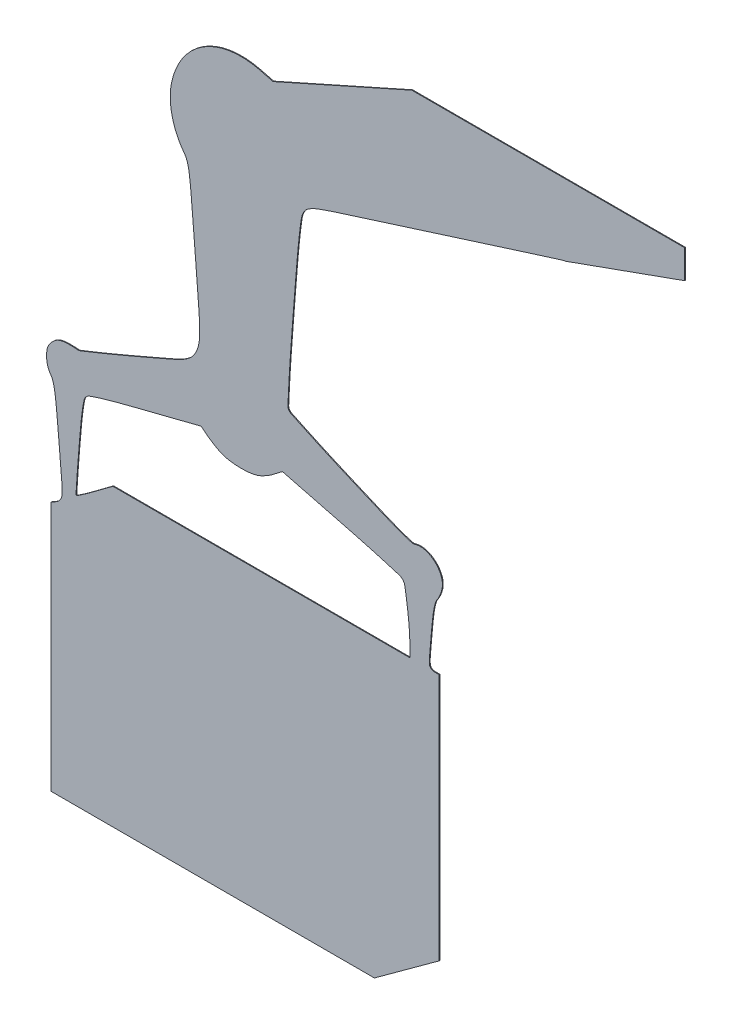
SolidWorks part; units mm, degrees
ref_plane "Front Plane" through (0, 0, 0) normal (0, 0, 1) x (1, 0, 0)
ref_plane "Top Plane" through (0, 0, 0) normal (0, 1, 0) x (1, 0, 0)
ref_plane "Right Plane" through (0, 0, 0) normal (1, 0, 0) x (0, 0, -1)
sketch "Sketch1" plane through (0, 0, 0) normal (0, 0, 1) x (1, 0, 0)
  line L0 (8013.7, 12087.9382) -> (6413.5, 11374.204)
  line L1 (6413.5, 11374.204) -> (6240.4799, 11418.3284)
  line L2 (3581.4, 5198.3404) -> (3505.2, 5153.328)
  line L3 (3505.2, 5153.328) -> (3505.2, 3516.464)
  line L4 (3505.2, 3516.464) -> (3505.2, 1879.6)
  line L5 (3505.2, 1879.6) -> (5622.3957, 1879.6)
  line L6 (5622.3957, 1879.6) -> (7739.5913, 1879.6)
  line L7 (7739.5913, 1879.6) -> (8162.3957, 2187.757)
  line L8 (8162.3957, 2187.757) -> (8585.2, 2495.9141)
  line L9 (8585.2, 2495.9141) -> (8585.2, 4118.157)
  line L10 (8585.2, 4118.157) -> (8585.2, 5740.4)
  line L11 (8585.2, 5740.4) -> (8521.7, 5740.4)
  line L12 (8585.2, 10732.9427) -> (9724.6877, 11094.0807)
  line L13 (11325.3923, 10020.3) -> (11488.731, 9831.6199)
  line L14 (11488.731, 9831.6199) -> (11633.909, 9664.1613)
  line L15 (11633.909, 9664.1613) -> (11756.8075, 9522.5883)
  line L16 (12065, 5921.1421) -> (12065, 5746.2841)
  line L17 (12065, 5746.2841) -> (11728.45, 5735.6247)
  line L18 (10878.3065, 5287.2778) -> (10807.7, 5143.5)
  line L19 (10807.7, 5143.5) -> (10800.0791, 4298.95)
  line L20 (10800.0791, 4298.95) -> (10792.4582, 3454.4)
  line L21 (10792.4582, 3454.4) -> (10695.5545, 3454.4)
  line L22 (10531.7254, 3401.7565) -> (10464.8, 3349.1129)
  line L23 (10464.8, 3349.1129) -> (10464.8, 2906.3588)
  line L24 (10464.8, 2906.3588) -> (10464.8, 2463.6046)
  line L25 (10464.8, 2463.6046) -> (13671.55, 2470.0523)
  line L26 (13671.55, 2470.0523) -> (16878.3, 2476.5)
  line L27 (16878.3, 2476.5) -> (16878.3, 2904.1918)
  line L28 (16878.3, 2904.1918) -> (16878.3, 3331.8836)
  line L29 (16878.3, 3331.8836) -> (16807.0336, 3393.1418)
  line L30 (16650.3866, 3454.4) -> (16565.006, 3454.4)
  line L31 (16565.006, 3454.4) -> (16556.553, 4288.879)
  line L32 (16556.553, 4288.879) -> (16548.1, 5123.358)
  line L33 (16548.1, 5123.358) -> (16459.2, 5297.5729)
  line L34 (15549.4837, 5740.4) -> (15265.4, 5740.4)
  line L35 (15265.4, 5740.4) -> (15265.4, 5904.521)
  line L36 (15265.4, 5904.521) -> (15265.4, 6068.642)
  line L37 (15265.4, 6068.642) -> (15365.7226, 6095.656)
  line L38 (13392.4905, 11080.3188) -> (13249.1836, 11204.4862)
  line L39 (13249.1836, 11204.4862) -> (12978.5872, 11438.7764)
  line L40 (12978.5872, 11438.7764) -> (12661.0677, 11713.6338)
  line L41 (12661.0677, 11713.6338) -> (12331.7, 11998.6859)
  line L42 (6416.8526, 6925.3764) -> (6535.7005, 7016.0951)
  line L43 (6535.7005, 7016.0951) -> (7300.1003, 6820.8399)
  line L44 (8204.2, 5847.005) -> (8204.2, 5740.4)
  line L45 (8204.2, 5740.4) -> (6261.0664, 5740.4)
  line L46 (6261.0664, 5740.4) -> (4317.9329, 5740.4)
  line L47 (4317.9329, 5740.4) -> (4083.0164, 5565.3869)
  line L48 (4740.2597, 6813.0046) -> (5473.7, 6998.8611)
  line L49 (5473.7, 6998.8611) -> (5549.9, 6937.2032)
  arc A0 (10252.0935, 13323.4899) -> (10114.6709, 13270.5908) centre (10485.9798, 12510.9446) ccw
  arc A1 (10114.6709, 13270.5908) -> (9972.416, 13189.4765) centre (10680.5693, 12112.8443) ccw
  arc A2 (9972.416, 13189.4765) -> (9841.3535, 13090.8097) centre (10682.7363, 12109.5526) ccw
  arc A3 (9841.3535, 13090.8097) -> (9737.5944, 12985.0784) centre (10402.6249, 12436.2301) ccw
  arc A4 (9737.5944, 12985.0784) -> (9696.7306, 12934.3409) centre (11838.9299, 11250.8474) ccw
  arc A5 (9696.7306, 12934.3409) -> (9660.7452, 12887.0372) centre (11182.0651, 11767.0583) ccw
  arc A6 (9660.7452, 12887.0372) -> (9631.8231, 12846.7566) centre (11340.1137, 11650.7039) ccw
  arc A7 (9631.8231, 12846.7566) -> (9623.2944, 12829.8192) centre (9685.8203, 12808.9505) ccw
  arc A8 (9608.6668, 12813.478) -> (9623.2944, 12829.8192) centre (9597.0774, 12838.5694) ccw
  arc A9 (9146.6008, 12600.2811) -> (9608.6668, 12813.478) centre (-255792.6689, 587415.7862) ccw
  arc A10 (8627.9063, 12363.6155) -> (9146.6008, 12600.2811) centre (-21976.6937, 80125.7388) ccw
  arc A11 (8013.7, 12087.9382) -> (8627.9063, 12363.6155) centre (-50634.9118, 143578.5359) ccw
  arc A12 (6240.4799, 11418.3284) -> (5850.1835, 11439.2224) centre (5992.7754, 10447.0343) ccw
  arc A13 (5850.1835, 11439.2224) -> (5494.1407, 11306.9205) centre (5977.9589, 10550.1298) ccw
  arc A14 (5494.1407, 11306.9205) -> (5225.1613, 11039.5959) centre (5976.1825, 10552.9105) ccw
  arc A15 (5225.1613, 11039.5959) -> (5081.729, 10677.5348) centre (6056.6861, 10500.7418) ccw
  arc A16 (5081.729, 10677.5348) -> (5069.2279, 10499.192) centre (5887.2837, 10531.4592) ccw
  arc A17 (5069.2279, 10499.192) -> (5094.762, 10316.1951) centre (6001.1767, 10535.9499) ccw
  arc A18 (5094.762, 10316.1951) -> (5155.9621, 10141.4417) centre (6005.0064, 10536.8769) ccw
  arc A19 (5155.9621, 10141.4417) -> (5249.0238, 9987.4979) centre (5913.2895, 10494.1589) ccw
  arc A20 (5290.0091, 9907.7948) -> (5249.0238, 9987.4979) centre (5046.2606, 9832.8428) ccw
  arc A21 (5315.7822, 9792.197) -> (5290.0091, 9907.7948) centre (4572.3498, 9687.1167) ccw
  arc A22 (5339.6477, 9581.5701) -> (5315.7822, 9792.197) centre (1511.3526, 9254.463) ccw
  arc A23 (5387.4374, 9008.2307) -> (5339.6477, 9581.5701) centre (-132723.8185, -2215.1229) ccw
  arc A24 (5444.2516, 8287.1951) -> (5387.4374, 9008.2307) centre (-141614.0357, -2937.5546) ccw
  arc A25 (5453.9529, 8037.2024) -> (5444.2516, 8287.1951) centre (2108.123, 8032.5479) ccw
  arc A26 (5437.7012, 7894.2959) -> (5453.9529, 8037.2024) centre (4825.2122, 8036.3273) ccw
  arc A27 (5389.1535, 7775.4147) -> (5437.7012, 7894.2959) centre (5044.7167, 7985.4263) ccw
  arc A28 (5326.0361, 7700.1996) -> (5389.1535, 7775.4147) centre (5109.8117, 7945.7364) ccw
  arc A29 (5237.7634, 7638.9825) -> (5326.0361, 7700.1996) centre (5018.422, 8049.5155) ccw
  arc A30 (5073.2949, 7559.3773) -> (5237.7634, 7638.9825) centre (4159.0171, 9658.0261) ccw
  arc A31 (4610.1, 7359.1782) -> (5073.2949, 7559.3773) centre (-29746.8689, 87485.8651) ccw
  arc A32 (4334.7458, 7242.4947) -> (4610.1, 7359.1782) centre (-9242.0821, 39664.8458) ccw
  arc A33 (4096.6231, 7144.6356) -> (4334.7458, 7242.4947) centre (-3146.485, 25108.1009) ccw
  arc A34 (3889.0491, 7061.3988) -> (4096.6231, 7144.6356) centre (-17819.7268, 61498.6719) ccw
  arc A35 (3860.8, 7057.0498) -> (3889.0491, 7061.3988) centre (3865.4977, 7120.4567) ccw
  arc A36 (3860.8, 7057.0498) -> (3716.4797, 7061.0921) centre (3744.687, 5489.8355) ccw
  arc A37 (3716.4797, 7061.0921) -> (3622.0311, 7045.2863) centre (3722.3132, 6736.1395) ccw
  arc A38 (3622.0311, 7045.2863) -> (3551.7445, 7005.9035) centre (3685.5189, 6849.5675) ccw
  arc A39 (3551.7445, 7005.9035) -> (3488.5769, 6936.3069) centre (3794.8768, 6721.766) ccw
  arc A40 (3488.5769, 6936.3069) -> (3457.805, 6864.6105) centre (3645.0925, 6826.6792) ccw
  arc A41 (3457.805, 6864.6105) -> (3450.4111, 6771.1586) centre (3838.8017, 6787.4475) ccw
  arc A42 (3450.4111, 6771.1586) -> (3465.7418, 6676.7762) centre (3852.3965, 6788.0174) ccw
  arc A43 (3465.7418, 6676.7762) -> (3502.5934, 6602.0933) centre (3691.4327, 6741.7079) ccw
  arc A44 (3533.979, 6539.0185) -> (3502.5934, 6602.0933) centre (3339.8314, 6481.7581) ccw
  arc A45 (3556.1691, 6441.2229) -> (3533.979, 6539.0185) centre (2778.2021, 6316.1153) ccw
  arc A46 (3577.1122, 6278.5056) -> (3556.1691, 6441.2229) centre (980.0302, 6026.9454) ccw
  arc A47 (3607.2203, 5951.4839) -> (3577.1122, 6278.5056) centre (-30816.4909, 2947.0655) ccw
  arc A48 (3649.7229, 5451.7678) -> (3607.2203, 5951.4839) centre (-109531.738, -3923.0241) ccw
  arc A49 (3652.9653, 5317.7275) -> (3649.7229, 5451.7678) centre (2506.1316, 5357.0445) ccw
  arc A50 (3632.6405, 5249.1507) -> (3652.9653, 5317.7275) centre (3510.6509, 5322.6064) ccw
  arc A51 (3581.4, 5198.3404) -> (3632.6405, 5249.1507) centre (3506.5281, 5325.0886) ccw
  arc A52 (8480.1587, 5755.3705) -> (8521.7, 5740.4) centre (8521.7, 5805.5215) ccw
  arc A53 (8460.9594, 5792.4048) -> (8480.1587, 5755.3705) centre (8514.2653, 5796.5458) ccw
  arc A54 (8461.1407, 5879.9232) -> (8460.9594, 5792.4048) centre (9009.628, 5835.0276) ccw
  arc A55 (8487.1696, 6184.9) -> (8461.1407, 5879.9232) centre (52418.8007, 2281.8604) ccw
  arc A56 (8503.998, 6351.1916) -> (8487.1696, 6184.9) centre (15286.0693, 5580.8609) ccw
  arc A57 (8520.8311, 6459.8446) -> (8503.998, 6351.1916) centre (9849.6243, 6198.3509) ccw
  arc A58 (8540.4302, 6534.7426) -> (8520.8311, 6459.8446) centre (9137.479, 6338.4948) ccw
  arc A59 (8566.1292, 6586.1394) -> (8540.4302, 6534.7426) centre (8727.9397, 6473.1088) ccw
  arc A60 (8566.1292, 6586.1394) -> (8586.0423, 6620.1363) centre (8363.7479, 6727.511) ccw
  arc A61 (8586.0423, 6620.1363) -> (8604.792, 6663.9413) centre (8114.9065, 6847.7095) ccw
  arc A62 (8604.792, 6663.9413) -> (8619.7439, 6710.0428) centre (8103.2991, 6852.0638) ccw
  arc A63 (8619.7439, 6710.0428) -> (8628.0625, 6751.2394) centre (8326.364, 6790.7217) ccw
  arc A64 (8628.0625, 6751.2394) -> (8609.9912, 6880.2982) centre (8385.1807, 6783.0247) ccw
  arc A65 (8609.9912, 6880.2982) -> (8527.689, 6993.646) centre (8315.0012, 6752.6589) ccw
  arc A66 (8527.689, 6993.646) -> (8405.7893, 7060.4322) centre (8318.7225, 6756.8759) ccw
  arc A67 (8405.7893, 7060.4322) -> (8277.7285, 7060.4338) centre (8341.7561, 6837.1824) ccw
  arc A68 (8215.0088, 7061.0271) -> (8277.7285, 7060.4338) centre (8247.3673, 7166.2973) ccw
  arc A69 (8070.9305, 7109.9044) -> (8215.0088, 7061.0271) centre (8990.1228, 9582.6636) ccw
  arc A70 (7843.5906, 7199.8569) -> (8070.9305, 7109.9044) centre (10111.8858, 12600.338) ccw
  arc A71 (7427.6986, 7376.4141) -> (7843.5906, 7199.8569) centre (30708.8976, 61638.692) ccw
  arc A72 (7126.0979, 7507.9948) -> (7427.6986, 7376.4141) centre (18086.9105, 32220.2071) ccw
  arc A73 (6867.7759, 7625.5064) -> (7126.0979, 7507.9948) centre (13210.3966, 21225.6068) ccw
  arc A74 (6646.295, 7729.6413) -> (6867.7759, 7625.5064) centre (23423.9194, 43125.7729) ccw
  arc A75 (6619.656, 7753.2583) -> (6646.295, 7729.6413) centre (6673.6257, 7787.3015) ccw
  arc A76 (6608.2654, 7796.0011) -> (6619.656, 7753.2583) centre (6682.488, 7792.8917) ccw
  arc A77 (6619.9588, 8045.1713) -> (6608.2654, 7796.0011) centre (31411.9392, 6756.8423) ccw
  arc A78 (6640.9084, 8384.4014) -> (6619.9588, 8045.1713) centre (24012.1758, 7141.3547) ccw
  arc A79 (6678.9754, 8894.7506) -> (6640.9084, 8384.4014) centre (91266.7116, 2328.7473) ccw
  arc A80 (6725.5817, 9475.2788) -> (6678.9754, 8894.7506) centre (116567.3834, 364.7551) ccw
  arc A81 (6756.6674, 9797.1308) -> (6725.5817, 9475.2788) centre (18632.8341, 8487.6592) ccw
  arc A82 (6782.8885, 9999.8092) -> (6756.6674, 9797.1308) centre (12147.669, 9202.7171) ccw
  arc A83 (6810.5265, 10087.8443) -> (6782.8885, 9999.8092) centre (7075.3066, 9956.3622) ccw
  arc A84 (6877.5131, 10162.6919) -> (6810.5265, 10087.8443) centre (6979.7001, 10003.8379) ccw
  arc A85 (7000.4666, 10223.631) -> (6877.5131, 10162.6919) centre (7211.1499, 9644.0393) ccw
  arc A86 (7268.1977, 10314.8144) -> (7000.4666, 10223.631) centre (9369.4248, 3706.5838) ccw
  arc A87 (8585.2, 10732.9427) -> (7268.1977, 10314.8144) centre (480922.4875, -1479297.7053) ccw
  arc A88 (10039.6335, 11193.3354) -> (9724.6877, 11094.0807) centre (41776.314, -90059.8862) ccw
  arc A89 (10213.2818, 11247.4404) -> (10039.6335, 11193.3354) centre (26096.0439, -40033.4917) ccw
  arc A90 (10240.8074, 11251.8723) -> (10213.2818, 11247.4404) centre (10242.6891, 11152.4925) ccw
  arc A91 (10260.5056, 11243.2311) -> (10240.8074, 11251.8723) centre (10241.2933, 11226.2078) ccw
  arc A92 (10436.4002, 11044.1096) -> (10260.5056, 11243.2311) centre (-55151.9765, -46716.3766) ccw
  arc A93 (10710.0413, 10730.9018) -> (10436.4002, 11044.1096) centre (-29133.5032, -23803.1693) ccw
  arc A94 (11325.3923, 10020.3) -> (10710.0413, 10730.9018) centre (-782064.5862, -676399.9684) ccw
  arc A95 (11756.8075, 9522.5883) -> (11789.3396, 9485.6066) centre (14689.5852, 12069.6981) ccw
  arc A96 (11812.1705, 9454.6385) -> (11789.3396, 9485.6066) centre (11633.8921, 9347.1044) ccw
  arc A97 (11822.1641, 9426.8225) -> (11812.1705, 9454.6385) centre (11747.7883, 9415.8045) ccw
  arc A98 (11821.5624, 9394.1164) -> (11822.1641, 9426.8225) centre (11723.9364, 9412.2711) ccw
  arc A99 (11810.0346, 9345.9066) -> (11821.5624, 9394.1164) centre (11342.1585, 9483.2666) ccw
  arc A100 (11810.0346, 9345.9066) -> (11782.3343, 9160.164) centre (12467.2666, 9152.9551) ccw
  arc A101 (11782.3343, 9160.164) -> (11769.9325, 7807.8605) centre (511149.4342, 3904.3043) ccw
  arc A102 (11769.9325, 7807.8605) -> (11760.8652, 6444.787) centre (597277.8939, 3231.462) ccw
  arc A103 (11760.8652, 6444.787) -> (11786.1076, 6284.962) centre (12262.0517, 6442.0373) ccw
  arc A104 (11786.1076, 6284.962) -> (11821.5015, 6213.5927) centre (12054.1125, 6373.4113) ccw
  arc A105 (11821.5015, 6213.5927) -> (11876.4599, 6152.2101) centre (12086.9828, 6395.9953) ccw
  arc A106 (11876.4599, 6152.2101) -> (11941.1162, 6110.2415) centre (12061.4872, 6366.4716) ccw
  arc A107 (11941.1162, 6110.2415) -> (12004.9254, 6096) centre (12004.9254, 6246.07) ccw
  arc A108 (12038.9372, 6089.5184) -> (12004.9254, 6096) centre (12004.9254, 6003.522) ccw
  arc A109 (12056.4684, 6071.1672) -> (12038.9372, 6089.5184) centre (12027.7812, 6061.3114) ccw
  arc A110 (12063.6881, 6030.9017) -> (12056.4684, 6071.1672) centre (11929.9621, 6027.7043) ccw
  arc A111 (12065, 5921.1421) -> (12063.6881, 6030.9017) centre (7472.8247, 5921.1403) ccw
  arc A112 (11728.45, 5735.6247) -> (11550.417, 5727.8291) centre (11961.6078, -1625.9564) ccw
  arc A113 (11550.417, 5727.8291) -> (11435.3917, 5716.5779) centre (11627.9007, 4342.0797) ccw
  arc A114 (11435.3917, 5716.5779) -> (11350.1207, 5699.1338) centre (11531.825, 5028.0536) ccw
  arc A115 (11350.1207, 5699.1338) -> (11274.4909, 5672.0445) centre (11482.2723, 5211.0652) ccw
  arc A116 (11274.4909, 5672.0445) -> (11154.2429, 5604.1277) centre (11587.8603, 4976.8094) ccw
  arc A117 (11154.2429, 5604.1277) -> (11044.3142, 5513.8063) centre (11642.236, 4898.1424) ccw
  arc A118 (11044.3142, 5513.8063) -> (10950.5394, 5406.2939) centre (11645.4647, 4894.816) ccw
  arc A119 (10950.5394, 5406.2939) -> (10878.3065, 5287.2778) centre (11581.2624, 4942.0696) ccw
  arc A120 (10695.5545, 3454.4) -> (10651.0085, 3450.8331) centre (10695.5546, 3174.4539) ccw
  arc A121 (10651.0085, 3450.8331) -> (10606.7287, 3440.2148) centre (10699.0047, 3153.048) ccw
  arc A122 (10606.7287, 3440.2148) -> (10565.9141, 3423.5009) centre (10693.5689, 3169.9638) ccw
  arc A123 (10565.9141, 3423.5009) -> (10531.7254, 3401.7565) centre (10657.1373, 3242.3212) ccw
  arc A124 (16807.0336, 3393.1418) -> (16771.4902, 3418.8051) centre (16638.067, 3196.5702) ccw
  arc A125 (16771.4902, 3418.8051) -> (16732.0332, 3438.1938) centre (16636.5676, 3194.0731) ccw
  arc A126 (16732.0332, 3438.1938) -> (16690.9027, 3450.321) centre (16641.1762, 3205.858) ccw
  arc A127 (16690.9027, 3450.321) -> (16650.3866, 3454.4) centre (16650.3868, 3251.1402) ccw
  arc A128 (16459.2, 5297.5729) -> (16314.3837, 5504.6466) centre (15643.7069, 4881.4355) ccw
  arc A129 (16314.3837, 5504.6466) -> (16130.4, 5640.928) centre (15857.3197, 5079.9297) ccw
  arc A130 (16130.4, 5640.928) -> (15884.5429, 5716.4253) centre (15766.0031, 4892.3347) ccw
  arc A131 (15884.5429, 5716.4253) -> (15549.4837, 5740.4) centre (15549.483, 3387.088) ccw
  arc A132 (15365.7226, 6095.656) -> (15410.5662, 6111.7521) centre (15289.7122, 6377.9358) ccw
  arc A133 (15410.5662, 6111.7521) -> (15452.9987, 6135.1424) centre (15281.3646, 6396.3212) ccw
  arc A134 (15452.9987, 6135.1424) -> (15489.875, 6163.8537) centre (15292.7314, 6379.0246) ccw
  arc A135 (15489.875, 6163.8537) -> (15518.1226, 6195.8061) centre (15352.6349, 6313.6435) ccw
  arc A136 (15518.1226, 6195.8061) -> (15550.2306, 6279.2645) centre (15371.7777, 6300.0131) ccw
  arc A137 (15550.2306, 6279.2645) -> (15563.3097, 6453.967) centre (13428.7054, 6525.9335) ccw
  arc A138 (15563.3097, 6453.967) -> (15569.2132, 6784.0631) centre (5132.7208, 6805.6094) ccw
  arc A139 (15569.2132, 6784.0631) -> (15570.2, 7740.508) centre (-447823.9797, 7740.406) ccw
  arc A140 (15570.2, 7740.508) -> (15566.205, 8841.1327) centre (-136032.4961, 7740.5483) ccw
  arc A141 (15566.205, 8841.1327) -> (15544.1483, 9254.4713) centre (11070.5982, 8808.4942) ccw
  arc A142 (15544.1483, 9254.4713) -> (15485.8152, 9528.862) centre (14274.0208, 9127.8492) ccw
  arc A143 (15485.8152, 9528.862) -> (15361.9134, 9829.8) centre (13307.7318, 8808.0795) ccw
  arc A144 (15361.9134, 9829.8) -> (15295.8502, 9950.7613) centre (13751.7327, 9028.9181) ccw
  arc A145 (15295.8502, 9950.7613) -> (15227.9328, 10051.2647) centre (14366.556, 9395.9707) ccw
  arc A146 (15227.9328, 10051.2647) -> (15140.8281, 10155.1889) centre (14085.0351, 9181.8031) ccw
  arc A147 (15140.8281, 10155.1889) -> (15011.8922, 10289.8997) centre (11472.4681, 6773.1475) ccw
  arc A148 (15011.8922, 10289.8997) -> (14870.9251, 10426.7982) centre (11107.8805, 6410.8905) ccw
  arc A149 (14870.9251, 10426.7982) -> (14769.5661, 10511.6839) centre (14059.3937, 9560.7346) ccw
  arc A150 (14769.5661, 10511.6839) -> (14667.4575, 10578.1698) centre (14202.097, 9751.8201) ccw
  arc A151 (14667.4575, 10578.1698) -> (14528.3784, 10650.9897) centre (13406.3021, 8338.7078) ccw
  arc A152 (14528.3784, 10650.9897) -> (14342.7936, 10732.1781) centre (13405.938, 8337.9594) ccw
  arc A153 (14342.7936, 10732.1781) -> (14166.8032, 10790.8401) centre (13682.8845, 9045.7238) ccw
  arc A154 (14166.8032, 10790.8401) -> (13989.2088, 10830.1871) centre (13703.3883, 9119.6589) ccw
  arc A155 (13989.2088, 10830.1871) -> (13798.8905, 10853.2754) centre (13636.7725, 8720.9838) ccw
  arc A156 (13696.5101, 10866.9445) -> (13798.8905, 10853.2754) centre (13867.8067, 11759.6995) ccw
  arc A157 (13628.8842, 10891.5933) -> (13696.5101, 10866.9445) centre (13739.0895, 11088.857) ccw
  arc A158 (13553.9989, 10943.0508) -> (13628.8842, 10891.5933) centre (13868.5679, 11320.6198) ccw
  arc A159 (13392.4905, 11080.3188) -> (13553.9989, 10943.0508) centre (20463.7071, 19236.6031) ccw
  arc A160 (11948.983, 12332.8993) -> (12331.7, 11998.6859) centre (49274.9761, 54689.6872) ccw
  arc A161 (11691.2791, 12566.2248) -> (11948.983, 12332.8993) centre (20497.4202, 22033.4743) ccw
  arc A162 (11514.9817, 12735.1871) -> (11691.2791, 12566.2248) centre (17265.0916, 18558.4665) ccw
  arc A163 (11446.9252, 12821.6767) -> (11514.9817, 12735.1871) centre (11825.017, 13049.1667) ccw
  arc A164 (11446.9252, 12821.6767) -> (11280.838, 13038.5976) centre (10397.7407, 12190.4035) ccw
  arc A165 (11280.838, 13038.5976) -> (11077.6061, 13202.0415) centre (10545.4808, 12332.3037) ccw
  arc A166 (11077.6061, 13202.0415) -> (10842.7129, 13306.545) centre (10561.9295, 12359.1884) ccw
  arc A167 (10842.7129, 13306.545) -> (10583.3984, 13350.0022) centre (10535.9778, 12271.6281) ccw
  arc A168 (10583.3984, 13350.0022) -> (10488.6588, 13351.4324) centre (10511.2508, 11709.3518) ccw
  arc A169 (10488.6588, 13351.4324) -> (10398.208, 13347.1957) centre (10507.5068, 11981.3768) ccw
  arc A170 (10398.208, 13347.1957) -> (10317.3298, 13337.797) centre (10488.8534, 12214.4726) ccw
  arc A171 (10317.3298, 13337.797) -> (10252.0935, 13323.4899) centre (10395.6874, 12824.6284) ccw
  arc A172 (5727.7, 6829.2305) -> (5826.5113, 6798.3403) centre (5900.303, 7207.8678) ccw
  arc A173 (5826.5113, 6798.3403) -> (5953.5319, 6784.1763) centre (5995.214, 7734.6095) ccw
  arc A174 (5953.5319, 6784.1763) -> (6086.2648, 6787.1201) centre (5997.6295, 7789.7097) ccw
  arc A175 (6086.2648, 6787.1201) -> (6203.3524, 6808.3705) centre (6028.8325, 7436.7617) ccw
  arc A176 (6203.3524, 6808.3705) -> (6247.9783, 6824.7617) centre (6124.841, 7091.066) ccw
  arc A177 (6247.9783, 6824.7617) -> (6305.1122, 6853.5845) centre (5854.2202, 7676.3265) ccw
  arc A178 (6305.1122, 6853.5845) -> (6364.4144, 6888.7157) centre (5810.3766, 7756.3264) ccw
  arc A179 (6364.4144, 6888.7157) -> (6416.8526, 6925.3764) centre (5952.7186, 7533.4239) ccw
  arc A180 (7616.8024, 6737.8543) -> (7300.1003, 6820.8399) centre (744.4734, -18843.5583) ccw
  arc A181 (7867.4556, 6667.2421) -> (7616.8024, 6737.8543) centre (4835.4283, -3615.4145) ccw
  arc A182 (8067.0813, 6606.9903) -> (7867.4556, 6667.2421) centre (3249.8214, -8992.6717) ccw
  arc A183 (8106.5513, 6583.0423) -> (8067.0813, 6606.9903) centre (8039.0959, 6516.3657) ccw
  arc A184 (8137.7779, 6521.845) -> (8106.5513, 6583.0423) centre (8025.9029, 6503.325) ccw
  arc A185 (8170.8196, 6300.1854) -> (8137.7779, 6521.845) centre (1261.4887, 5383.5388) ccw
  arc A186 (8195.929, 6060.9752) -> (8170.8196, 6300.1854) centre (3805.2957, 5721.0231) ccw
  arc A187 (8204.2, 5847.005) -> (8195.929, 6060.9752) centre (5432.3326, 5847.0033) ccw
  arc A188 (3992.2777, 5498.904) -> (4083.0164, 5565.3869) centre (-134.1554, 11226) ccw
  arc A189 (3914.379, 5444.3147) -> (3992.2777, 5498.904) centre (1872.3995, 8441.0894) ccw
  arc A190 (3846.4682, 5398.3879) -> (3914.379, 5444.3147) centre (-2684.2836, 15128.413) ccw
  arc A191 (3838.8142, 5398.9894) -> (3846.4682, 5398.3879) centre (3843.0211, 5403.5236) ccw
  arc A192 (3835.4262, 5407.4754) -> (3838.8142, 5398.9894) centre (3846.0639, 5406.8031) ccw
  arc A193 (3845.7389, 5568.6876) -> (3835.4262, 5407.4754) centre (109901.2083, -1296.575) ccw
  arc A194 (3858.4982, 5750.4205) -> (3845.7389, 5568.6876) centre (20524.7365, 4488.9839) ccw
  arc A195 (3875.4274, 5964.5869) -> (3858.4982, 5750.4205) centre (35946.9251, 3321.6807) ccw
  arc A196 (3900.5044, 6248.55) -> (3875.4274, 5964.5869) centre (28108.4279, 3967.6421) ccw
  arc A197 (3920.6727, 6417.0114) -> (3900.5044, 6248.55) centre (7250.9541, 5932.8698) ccw
  arc A198 (3940.3373, 6525.0037) -> (3920.6727, 6417.0114) centre (5439.9816, 6196.1433) ccw
  arc A199 (3964.0729, 6574.3585) -> (3940.3373, 6525.0037) centre (4056.4751, 6499.5357) ccw
  arc A200 (4011.6208, 6608.2203) -> (3964.0729, 6574.3585) centre (4048.7157, 6505.8189) ccw
  arc A201 (4151.4563, 6655.0134) -> (4011.6208, 6608.2203) centre (5031.2387, 3793.5541) ccw
  arc A202 (4369.3058, 6717.1608) -> (4151.4563, 6655.0134) centre (5784.0414, 1345.1004) ccw
  arc A203 (4740.2597, 6813.0046) -> (4369.3058, 6717.1608) centre (14833.9848, -33019.5514) ccw
  arc A204 (5549.9, 6937.2032) -> (5586.372, 6910.2467) centre (5875.5703, 7339.682) ccw
  arc A205 (5586.372, 6910.2467) -> (5633.5612, 6880.0523) centre (6253.2435, 7900.4927) ccw
  arc A206 (5633.5612, 6880.0523) -> (5683.2467, 6851.4439) centre (6271.6551, 7930.8083) ccw
  arc A207 (5683.2467, 6851.4439) -> (5727.7, 6829.2305) centre (6016.4694, 7462.6995) ccw
extrude "Boss-Extrude1" add sketch "Sketch1" along normal blind 10
scale "Scale1" bodies to scale 101 scale about centroid uniform scaling yes scale factor 0.046
sketch "Sketch2" plane through (0, 0, 5.23) normal (0, 0, 1) x (1, 0, 0)
  line L0 (10322.0306, 6841.4546) -> (10418.1131, 6875.8933)
  line L1 (10433.3626, 6862.6956) -> (10418.2116, 6875.808) construction
  line L2 (10322.0306, 6841.4546) -> (10292.0281, 6387.3884)
  line L3 (10292.0281, 6387.3884) -> (10677.2596, 6410.0491)
  line L4 (10677.2596, 6410.0491) -> (10661.0672, 6685.3199)
  line L5 (10661.0672, 6685.3199) -> (10558.9205, 6841.4546)
  line L6 (10558.9205, 6841.4546) -> (10418.1131, 6875.8933)
  arc A0 (10322.0306, 6841.4546) -> (10320.7644, 6841.2507) centre (10322.1171, 6836.8831) ccw construction
  arc A1 (10400.6067, 6891.1818) -> (10418.2116, 6875.808) centre (12117.6023, 8839.5941) ccw construction
extrude "Cut-Extrude1" cut sketch "Sketch2" against normal through all
sketch "Sketch3" plane through (0, 0, 5.23) normal (0, 0, 1) x (1, 0, 0)
  line L0 (10229.4838, 6884.3391) -> (10393.6994, 6884.3391)
  line L1 (10393.6994, 6867.1428) -> (10393.6994, 6884.3391)
  line L2 (10418.1131, 6875.8933) -> (10322.0306, 6841.4546) construction
  line L3 (10229.4838, 6884.3391) -> (10244.6878, 6944.8111)
  line L4 (10244.6878, 6944.8111) -> (10390.8166, 6955.6403)
  line L5 (10390.8166, 6955.6403) -> (10432.4372, 6872.2685)
  line L6 (10432.4372, 6872.2685) -> (10393.6994, 6867.1428)
  arc A0 (10219.5836, 6879.9136) -> (10247.8371, 6892.5948) centre (7521.7475, 12928.4811) ccw construction
extrude "Cut-Extrude2" cut sketch "Sketch3" against normal through all
